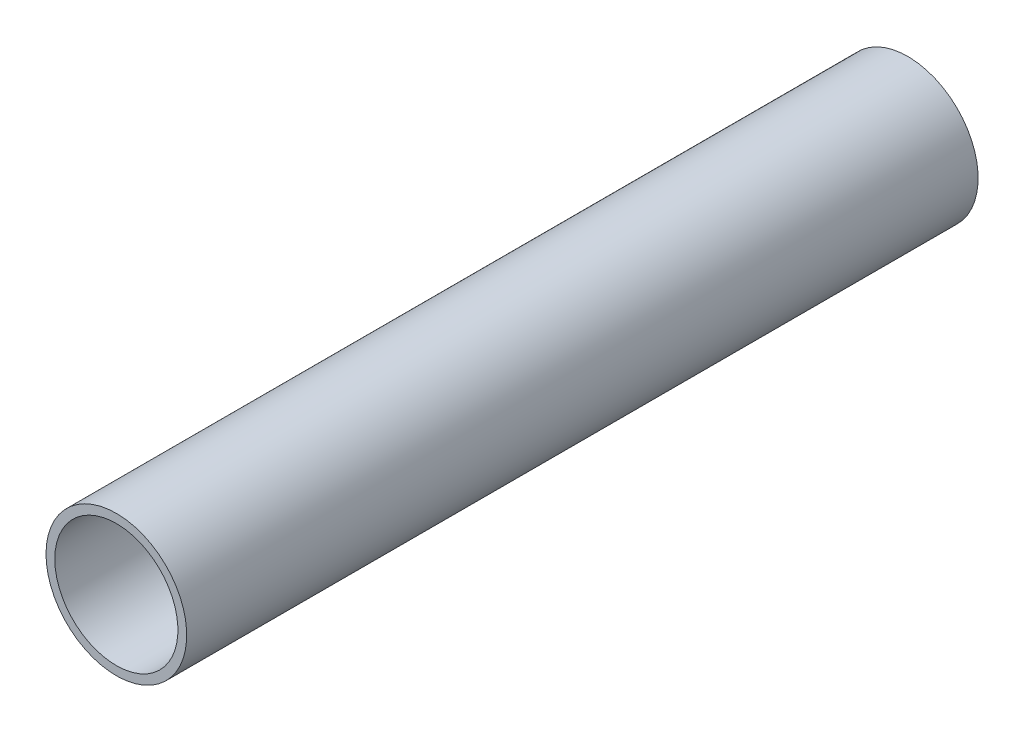
SolidWorks part; units mm, degrees
ref_plane "前视基准面" through (0, 0, 0) normal (0, 0, 1) x (1, 0, 0)
ref_plane "上视基准面" through (0, 0, 0) normal (0, 1, 0) x (1, 0, 0)
ref_plane "右视基准面" through (0, 0, 0) normal (1, 0, 0) x (0, 0, -1)
other "Configuration Table"
sketch "草图1" plane through (0, 0, 0) normal (0, 0, 1) x (1, 0, 0)
  circle A0 centre (0, 0) radius 7
  circle A1 centre (0, 0) radius 8
  dimension "D1" = 14
  dimension "D2" = 16
extrude "凸台-拉伸1" add sketch "草图1" along normal blind 90
